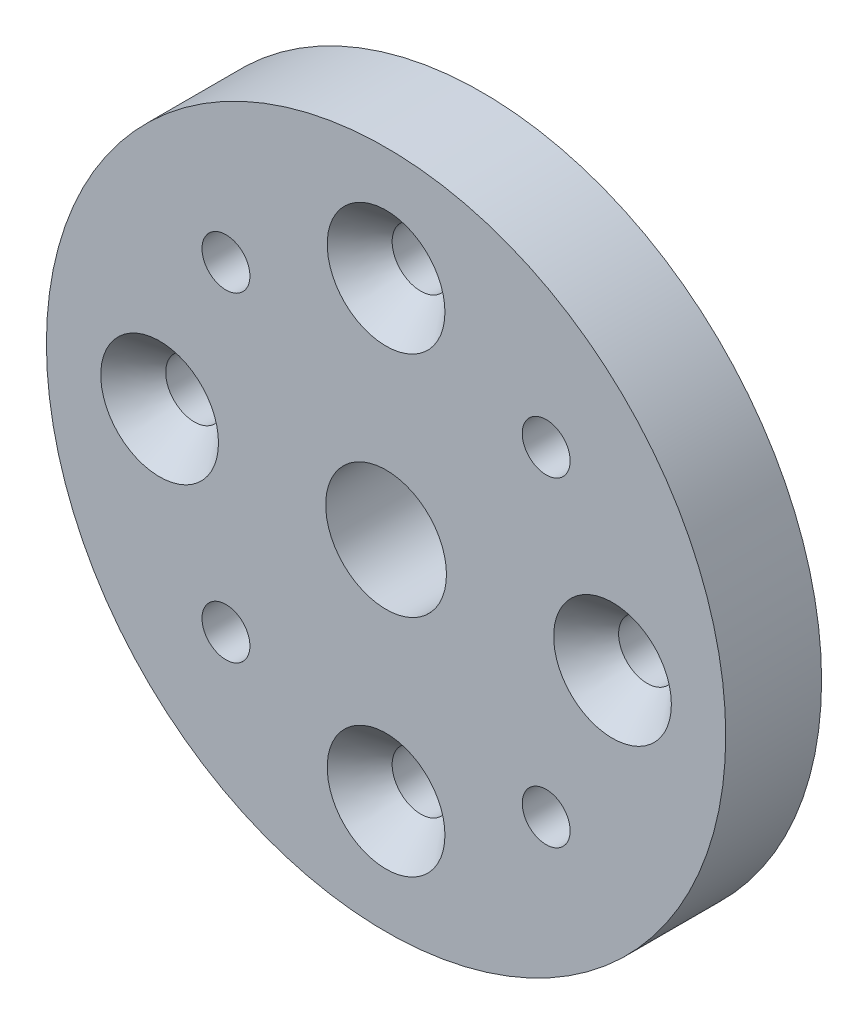
SolidWorks part; units mm, degrees
material "Balsa"
ref_plane "Front Plane" through (0, 0, 0) normal (0, 0, 1) x (1, 0, 0)
ref_plane "Top Plane" through (0, 0, 0) normal (0, 1, 0) x (1, 0, 0)
ref_plane "Right Plane" through (0, 0, 0) normal (1, 0, 0) x (0, 0, -1)
sketch "Sketch1" plane through (0, 0, 0) normal (0, 0, 1) x (1, 0, 0)
  circle A0 centre (0, 0) radius 22.5
  circle A1 centre (0, 0) radius 4
  circle A2 centre (0, 0) radius 15 construction
  circle A3 centre (0, 15) radius 1.8986
  circle A4 centre (10.6066, 10.6066) radius 1.5875
  circle A5 centre (15, 0) radius 1.8986
  circle A6 centre (10.6066, -10.6066) radius 1.5875
  circle A7 centre (0, -15) radius 1.8986
  circle A8 centre (-10.6066, -10.6066) radius 1.5875
  circle A9 centre (-15, 0) radius 1.8986
  circle A10 centre (-10.6066, 10.6066) radius 1.5875
  dimension "D1" = 45
  dimension "D2" = 8
  dimension "D3" = 30
  dimension "D4" = 3.7973
  dimension "D5" = 3.175
  dimension "D6" = 45
  dimension "D7" = 4
extrude "Boss-Extrude1" add sketch "Sketch1" along normal blind 6.35
other "Move Face1" [suppressed] parameters "D1"=0.08
chamfer "Chamfer1" distance 2.301 angle 41 4 edges at (1.8987, -15, 6.35) (-13.1014, 0, 6.35) (1.8986, 15, 6.35) (16.8986, 0, 6.35)
